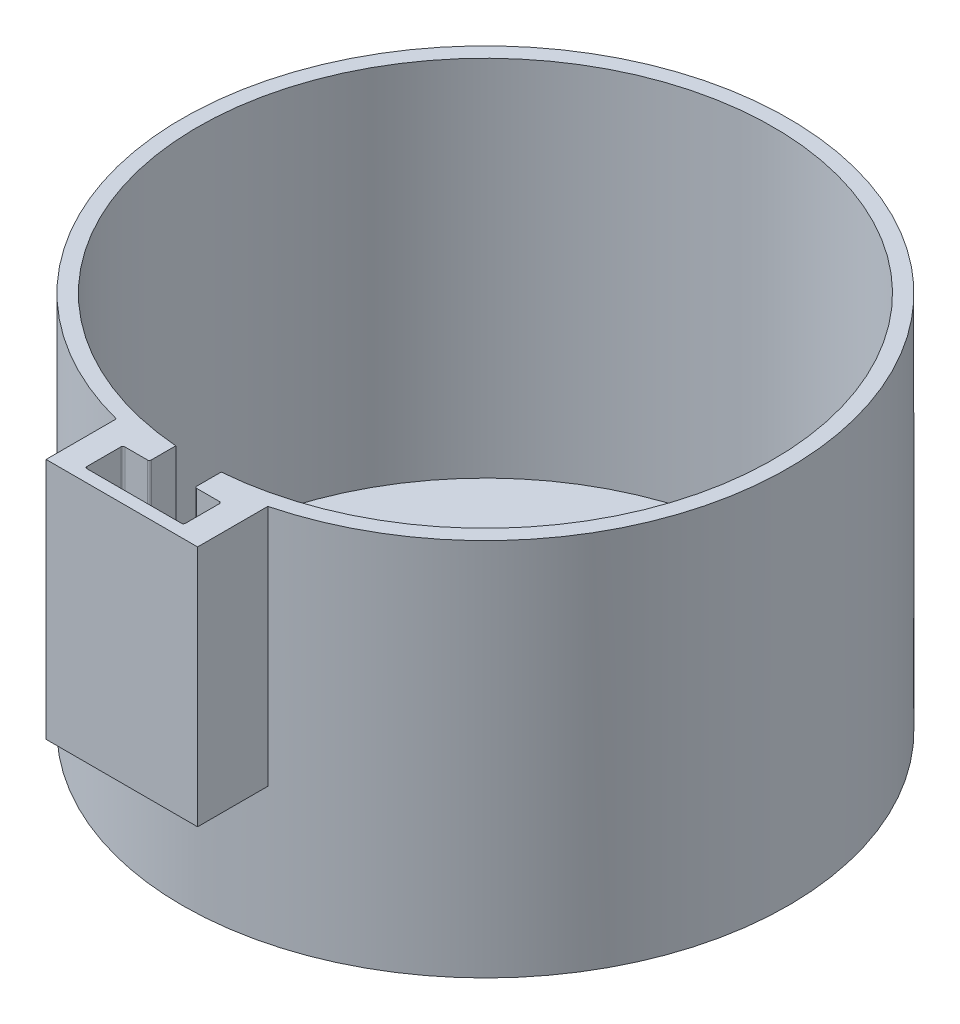
SolidWorks part; units mm, degrees
ref_plane "Front Plane" through (0, 0, 0) normal (0, 0, 1) x (1, 0, 0)
ref_plane "Top Plane" through (0, 0, 0) normal (0, 1, 0) x (1, 0, 0)
ref_plane "Right Plane" through (0, 0, 0) normal (1, 0, 0) x (0, 0, -1)
sketch "Sketch1" plane through (0, 0, 0) normal (0, 1, 0) x (1, 0, 0)
  circle A0 centre (0, 0) radius 40
extrude "Boss-Extrude1" add sketch "Sketch1" along normal blind 40 contours A0
sketch "Sketch2" plane through (0, 40, 0) normal (0, 1, 0) x (1, 0, 0)
  circle A0 centre (0, 0) radius 38
extrude "Cut-Extrude1" cut sketch "Sketch2" against normal blind 38
sketch "Sketch3" plane through (0, 2, 0) normal (0, 1, 0) x (1, 0, 0)
  line L0 (-38, 0) -> (38, 0) construction
  circle A1 centre (0, 0) radius 38 construction
  circle A2 centre (0, 0) radius 38 construction
  arc A4 (-14.0761, -35.2968) -> (14.0761, -35.2968) centre (0, -39.1212) cw
  arc A5 (-14.0761, -35.2968) -> (14.0761, -35.2968) centre (0, 0) ccw
extrude "Cut-Extrude2" cut sketch "Sketch3" against normal blind 38
sketch "Sketch4" plane through (0, 2, 0) normal (0, 1, 0) x (1, 0, 0)
  circle A0 centre (0, 0) radius 5
extrude "Cut-Extrude3" cut sketch "Sketch4" against normal blind 38
sketch "Sketch6" plane through (0, 0, 0) normal (0, -1, 0) x (1, 0, 0)
  circle A1 centre (-20, 0) radius 2
  circle A2 centre (20, 0) radius 2
extrude "Boss-Extrude2" add sketch "Sketch6" along normal blind 2
sketch "Sketch8" plane through (0, 40, 0) normal (0, 1, 0) x (1, 0, 0)
  circle A0 centre (0, 0) radius 43.4969
sketch "Sketch9" plane through (0, 40, 0) normal (0, 1, 0) x (1, 0, 0)
  circle A3 centre (0, 0) radius 40
  circle A4 centre (0, 0) radius 40
  circle A6 centre (0, 0) radius 38 construction
  circle A7 centre (0, 0) radius 38
  dimension "D1" = 0
extrude "Boss-Extrude3" add sketch "Sketch9" along normal blind 10
sketch "Sketch10" plane through (0, 50, 0) normal (0, 1, 0) x (1, 0, 0)
  line L0 (0, 0) -> (0, -38) construction
  line L4 (0, -38) -> (10, -38)
  line L6 (10, -38) -> (10, -48)
  line L8 (0, -38) -> (-10, -38)
  line L9 (-10, -38) -> (-10, -48)
  line L10 (-10, -48) -> (10, -48)
  circle A0 centre (0, 0) radius 38 construction
extrude "Boss-Extrude4" add sketch "Sketch10" against normal blind 32 contours L8 L9 L10 L6 L4
sketch "Sketch11" plane through (0, 50, 0) normal (0, 1, 0) x (1, 0, 0)
  line L0 (0, -48) -> (0, -38) construction
  line L1 (-10, -48) -> (10, -48) construction
  line L2 (-10, -43.3649) -> (10, -43.3649) construction
  line L3 (-10, -38.7298) -> (-10, -48) construction
  line L4 (10, -38.7298) -> (10, -48) construction
  line L8 (-3, -36.8649) -> (3, -36.8649)
  line L10 (-3, -36.8649) -> (-3, -41.3649)
  line L11 (3, -36.8649) -> (3, -41.3649)
  line L12 (3, -41.3649) -> (6.5, -41.3649)
  line L13 (6.5, -41.3649) -> (6.5, -46.3649)
  line L14 (-3, -41.3649) -> (-6.5, -41.3649)
  line L15 (-6.5, -41.3649) -> (-6.5, -46.3649)
  line L16 (-6.5, -46.3649) -> (6.5, -46.3649)
  arc A0 (14.0761, -35.2968) -> (-14.0761, -35.2968) centre (0, 0) ccw construction
  dimension "D1" = 13
  dimension "D2" = 5
  dimension "D3" = 4.5
  dimension "D4" = 6
extrude "Cut-Extrude4" cut sketch "Sketch11" against normal blind 30
fillet "Fillet1" radius 0.25 6 edges at (-3, 35, 41.3649) (3, 35, 41.3649) (6.5, 35, 41.3649) (-6.5, 35, 41.3649) (6.5, 35, 46.3649) (-6.5, 35, 46.3649)
sketch "Sketch13" plane through (0, 0, 0) normal (0, -1, 0) x (1, 0, 0)
  circle A0 centre (-30, 0) radius 3
  circle A1 centre (30, 0) radius 3
extrude "Cut-Extrude5" cut sketch "Sketch13" against normal blind 10
